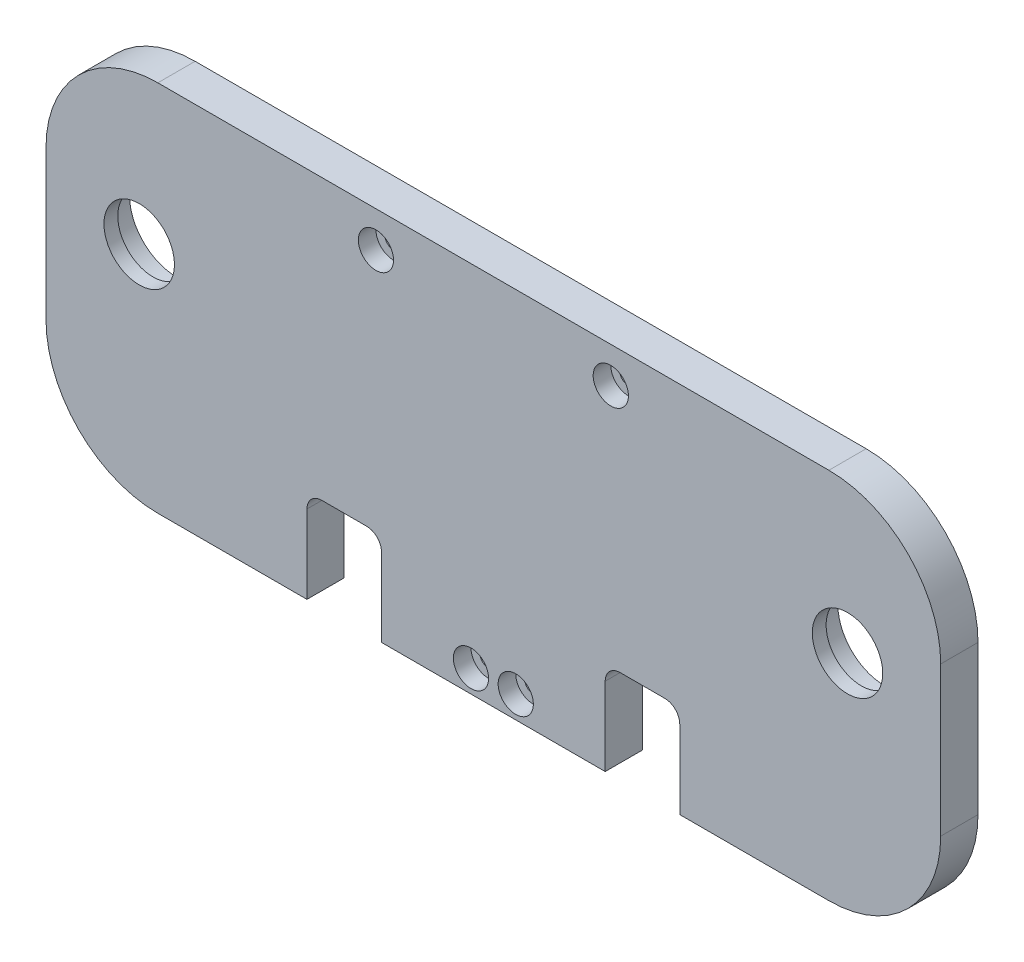
SolidWorks part; units mm, degrees
ref_plane "Front Plane" through (0, 0, 0) normal (0, 0, 1) x (1, 0, 0)
ref_plane "Top Plane" through (0, 0, 0) normal (0, 1, 0) x (1, 0, 0)
ref_plane "Right Plane" through (0, 0, 0) normal (1, 0, 0) x (0, 0, -1)
sketch "Sketch1" plane through (0, 0, 0) normal (0, 0, 1) x (1, 0, 0)
  line L0 (-57.15, 31.75) -> (57.15, 31.75)
  line L1 (76.2, 12.7) -> (76.2, -12.7)
  line L2 (-76.2, 12.7) -> (-76.2, -12.7)
  line L3 (-57.15, -31.75) -> (57.15, -31.75)
  arc A0 (-76.2, 12.7) -> (-57.15, 31.75) centre (-57.15, 12.7) cw
  arc A1 (57.15, 31.75) -> (76.2, 12.7) centre (57.15, 12.7) cw
  arc A2 (76.2, -12.7) -> (57.15, -31.75) centre (57.15, -12.7) cw
  arc A3 (-57.15, -31.75) -> (-76.2, -12.7) centre (-57.15, -12.7) cw
  point P8 (0, 31.75)
  point P10 (-76.2, 0)
  point P17 (0, -31.75)
  point P18 (76.2, 0)
  dimension "D2" = 25.4
  dimension "D1" = 63.5
  dimension "D3" = 152.4
extrude "Boss-Extrude1" add sketch "Sketch1" along normal blind 6.35
hole_wizard "CBORE for #00 Binding Head Machine Screw1" positions "Sketch4" profile "Sketch5" counterbore size "#00" standard "ANSI Inch" end condition through all
sketch "Sketch4" plane through (0, 0, 6.35) normal (0, 0, 1) x (1, 0, 0)
  line L0 (57.15, 31.75) -> (-57.15, 31.75) construction
  line L1 (-57.15, -31.75) -> (57.15, -31.75) construction
  point P0 (-20, 25.65)
  point P2 (20, 25.65)
  point P4 (3.81, -27.94)
  point P6 (-3.81, -27.94)
  dimension "D1" = 40
  dimension "D2" = 7.62
  dimension "D3" = 3.81
  dimension "D4" = 20
  dimension "D5" = 6.1
  dimension "D6" = 3.81
sketch "Sketch5" plane through (-20, 25.65, 6.35) normal (1, 0, 0) x (0, -1, 0)
  line L0 (0, 0) -> (0, 6.35)
  line L1 (0, 6.35) -> (1.5, 6.35)
  line L3 (1.5, 6.35) -> (1.5, 3)
  line L4 (1.5, 3) -> (3, 3)
  line L5 (3, 3) -> (3, 0)
  line L7 (3, 0) -> (0, 0)
  line L11 (0, -6.35) -> (0, 107.95) construction
  dimension "Thru Hole Dia." = 3
  dimension "Thru Hole Depth" = 6.35
  dimension "C'Bore Dia." = 6
  dimension "C'Bore Depth" = 3
sketch "Sketch6" plane through (0, 0, 0) normal (0, 0, -1) x (-1, 0, 0)
  line L0 (-76.2, -12.7) -> (76.2, -12.7)
  line L1 (-31.75, -31.75) -> (-31.75, -12.7)
  line L2 (57.15, -31.75) -> (-57.15, -31.75) construction
  line L3 (-31.75, -12.7) -> (-19.05, -12.7)
  line L4 (-19.05, -12.7) -> (-19.05, -31.75)
  line L5 (-19.05, -31.75) -> (-31.75, -31.75)
  line L6 (-76.2, -12.7) -> (-76.2, 12.7) construction
  line L7 (0, 3.4925) -> (0, -3.4925) construction
  line L8 (19.05, -31.75) -> (31.75, -31.75)
  line L9 (19.05, -12.7) -> (19.05, -31.75)
  line L10 (31.75, -31.75) -> (31.75, -12.7)
  line L11 (-31.75, -15.875) -> (-19.05, -15.875)
  line L12 (19.05, -15.875) -> (31.75, -15.875)
  line M23 (-57.15, -31.75) -> (57.15, -31.75)
  dimension "D1" = 12.7
  dimension "D2" = 44.45
  dimension "D3" = 3.175
extrude "Cut-Extrude1" cut sketch "Sketch6" against normal up to surface (6.35 mm away) contours L4 L0 L1 M23 | L10 L0 L9 M23
fillet "Fillet2" radius 2.54 4 edges at (-31.75, -15.875, 3.175) (-19.05, -15.875, 3.175) (19.05, -15.875, 3.175) (31.75, -15.875, 3.175)
sketch "Sketch10" plane through (0, 0, 0) normal (0, 0, -1) x (-1, 0, 0)
  line L0 (-76.2, -12.7) -> (-76.2, 12.7) construction
  line L1 (-57.15, 31.75) -> (57.15, 31.75) construction
  line L2 (0, 3.4925) -> (0, -3.4925) construction
  circle A0 centre (-60.325, 6.35) radius 7.493
  circle A2 centre (60.325, 6.35) radius 7.493
  dimension "D1" = 14.986
  dimension "D2" = 15.875
  dimension "D3" = 25.4
extrude "Cut-Extrude2" [suppressed] cut sketch "Sketch10" against normal through all
sketch "Sketch11" [suppressed] plane through (0, 0, 6.35) normal (0, 0, 1) x (1, 0, 0)
  line L0 (56.575, 12.8452) -> (58.3744, 20.7917) construction
  line L1 (58.3744, 20.7917) -> (56.575, 12.8452) construction
  line L2 (64.075, 12.8452) -> (62.2756, 20.7917) construction
  line L3 (54.5639, 11.1521) -> (56.8271, 21.1467)
  line L4 (66.077, 11.1521) -> (63.8138, 21.1467)
  line L5 (61.6032, 13.7403) -> (71.3904, 16.7776)
  line L6 (67.3597, 3.7697) -> (74.8837, 10.727)
  line L7 (67.3643, 8.9382) -> (74.8883, 1.9809)
  line L8 (61.6078, -1.0324) -> (71.3949, -4.0698)
  line L9 (66.0861, 1.5479) -> (63.8229, -8.4467)
  line L10 (54.573, 1.5479) -> (56.8362, -8.4467)
  line L11 (59.0468, -1.0403) -> (49.2596, -4.0776)
  line L12 (53.2903, 8.9303) -> (45.7663, 1.973)
  line L13 (53.2857, 3.7618) -> (45.7617, 10.7191)
  line L14 (59.0422, 13.7324) -> (49.2551, 16.7698)
  circle A0 centre (60.325, 6.35) radius 7.5 construction
  arc A1 (58.3744, 20.7917) -> (62.2756, 20.7917) centre (60.325, 20.35) cw construction
  circle A2 centre (60.325, 6.35) radius 7.493 construction
  arc A3 (56.8271, 21.1467) -> (63.8138, 21.1467) centre (60.3204, 20.3557) cw
  arc A4 (71.3904, 16.7776) -> (74.8837, 10.727) centre (72.452, 13.3568) cw
  arc A5 (74.8883, 1.9809) -> (71.3949, -4.0698) centre (72.4566, -0.6489) cw
  arc A6 (63.8229, -8.4467) -> (56.8362, -8.4467) centre (60.3296, -7.6557) cw
  arc A7 (49.2596, -4.0776) -> (45.7663, 1.973) centre (48.198, -0.6568) cw
  arc A8 (45.7617, 10.7191) -> (49.2551, 16.7698) centre (48.1934, 13.3489) cw
  point P19 (60.3204, 23.9375)
  point P20 (60.325, 22.35)
  point P48 (60.325, 6.35)
  dimension "D1" = 1.5875
  dimension "D2" = 1.5875
extrude "Cut-Extrude3" [suppressed] cut sketch "Sketch11" against normal blind 2.54
fillet "Fillet3" [suppressed] radius 1.5875
mirror "Mirror1" [suppressed] about plane through (0, 0, 0) normal (1, 0, 0)
hole_wizard "CBORE for #00 Binding Head Machine Screw2" positions "Sketch8" profile "Sketch9" counterbore size "#00" standard "ANSI Inch" end condition through all
sketch "Sketch8" plane through (0, 0, 0) normal (0, 0, 1) x (1, 0, 0)
  line L0 (-76.2, 12.7) -> (-76.2, -12.7) construction
  line L1 (57.15, 31.75) -> (-57.15, 31.75) construction
  line L2 (76.2, -12.7) -> (76.2, 12.7) construction
  point P0 (-60.325, 6.35)
  point P3 (60.325, 6.35)
  dimension "D1" = 15.875
  dimension "D2" = 25.4
  dimension "D3" = 25.4
  dimension "D4" = 15.875
sketch "Sketch9" plane through (-60.325, 6.35, 0) normal (1, 0, 0) x (0, 1, 0)
  line L0 (0, 0) -> (0, 6.35)
  line L1 (0, 6.35) -> (6, 6.35)
  line L3 (6, 6.35) -> (6, 4)
  line L4 (6, 4) -> (8, 4)
  line L5 (8, 4) -> (8, 0)
  line L7 (8, 0) -> (0, 0)
  line L11 (0, -6.35) -> (0, 107.95) construction
  dimension "Thru Hole Dia." = 12
  dimension "Thru Hole Depth" = 6.35
  dimension "C'Bore Dia." = 16
  dimension "C'Bore Depth" = 4
